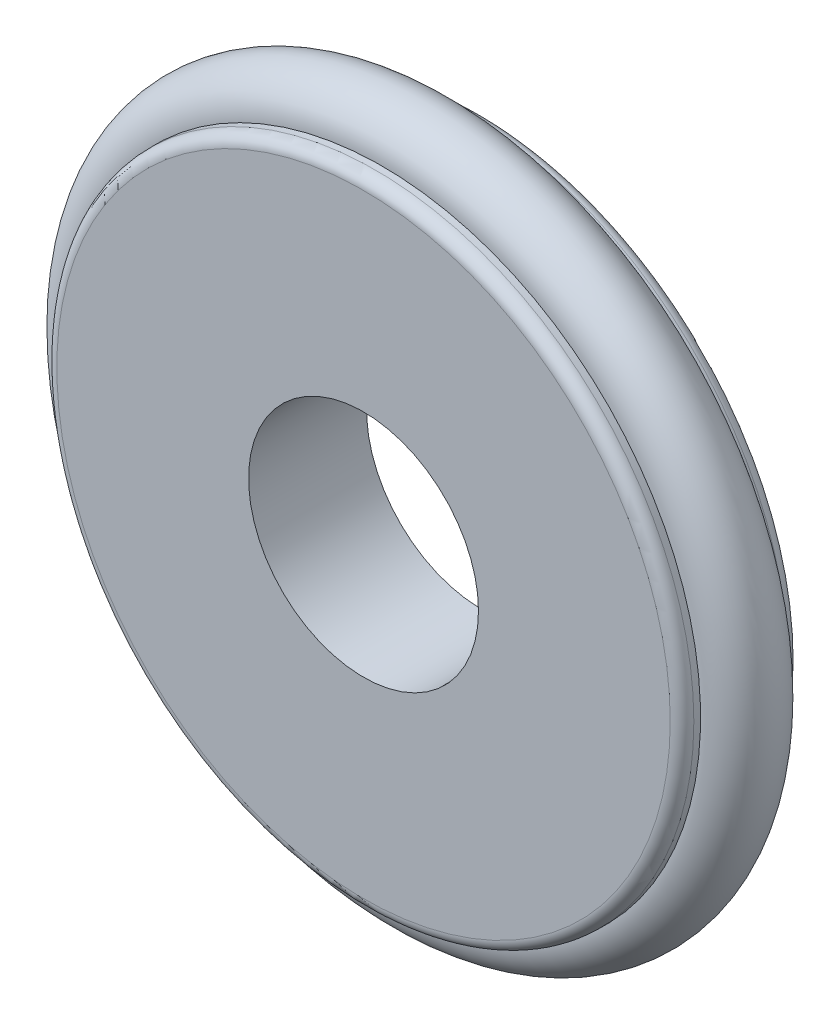
SolidWorks part; units mm, degrees
ref_plane "Ön Düzlem" through (0, 0, 0) normal (0, 0, 1) x (1, 0, 0)
ref_plane "Üst Düzlem" through (0, 0, 0) normal (0, 1, 0) x (1, 0, 0)
ref_plane "Sağ Düzlem" through (0, 0, 0) normal (1, 0, 0) x (0, 0, -1)
sketch "Çizim1" plane through (0, 0, 0) normal (0, 0, 1) x (1, 0, 0)
  circle A0 centre (0, 0) radius 27
  dimension "D1" = 54
extrude "Yükseklik-Ekstrüzyon1" add sketch "Çizim1" along normal blind 10
sketch "Çizim2" plane through (0, 0, 10) normal (0, 0, 1) x (1, 0, 0)
  circle A0 centre (0, 0) radius 9.7444
extrude "Kes-Ekstrüzyon1" cut sketch "Çizim2" against normal blind 10
sketch "Çizim3" plane through (0, 0, 0) normal (1, 0, 0) x (0, 0, -1)
  line L0 (0, 0) -> (-36.2892, 0) construction
  circle A0 centre (-5.2203, 26.9837) radius 3.2089
revolve "Kes-Döndür1" cut sketch "Çizim3" angle 360 about L0
fillet "Radyus1" radius 1 2 edges at (27, 0, 0) (27, 0, 10)
sketch "Çizim4" plane through (0, 0, 0) normal (1, 0, 0) x (0, 0, -1)
  line L0 (0, 0) -> (-33.9934, 0) construction
  circle A0 centre (-5.2231, 27.1035) radius 3.1954
revolve "Döndür1" add sketch "Çizim4" angle 360 about L0
